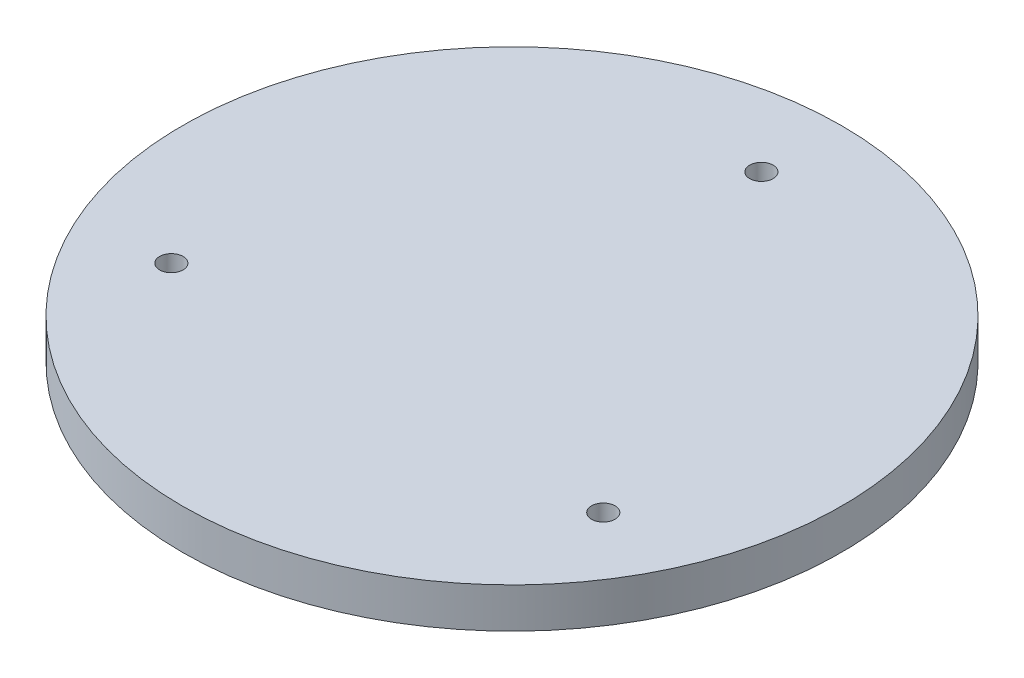
SolidWorks part; units mm, degrees
material "Pine"
ref_plane "Front Plane" through (0, 0, 0) normal (0, 0, 1) x (1, 0, 0)
ref_plane "Top Plane" through (0, 0, 0) normal (0, 1, 0) x (1, 0, 0)
ref_plane "Right Plane" through (0, 0, 0) normal (1, 0, 0) x (0, 0, -1)
sketch "Sketch1" plane through (0, 0, 0) normal (0, 1, 0) x (1, 0, 0)
  circle A0 centre (0, 0) radius 117.475
  dimension "D1" = 234.95
extrude "Boss-Extrude1" add sketch "Sketch1" along normal blind 14.2875
sketch "Sketch2" plane through (0, 14.2875, 0) normal (0, 1, 0) x (1, 0, 0)
  circle A0 centre (0, 0) radius 117.475 construction
  circle A1 centre (0, 88.9) radius 4.1783
  circle A2 centre (76.9897, -44.45) radius 4.1783
  circle A3 centre (-76.9897, -44.45) radius 4.1783
  point P15 (0, 0)
  dimension "D1" = 8.3566
  dimension "D2" = 88.9
  dimension "D3" = 3
extrude "Cut-Extrude1" cut sketch "Sketch2" against normal through all
